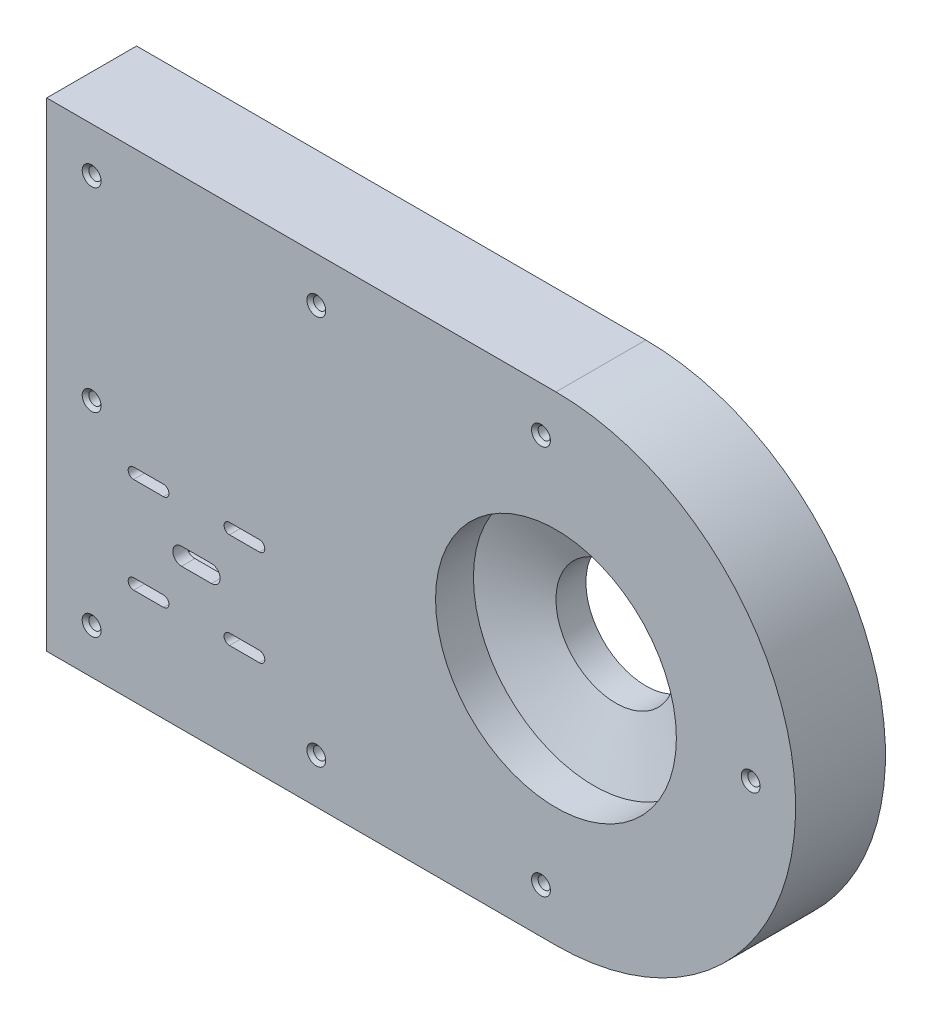
SolidWorks part; units mm, degrees
ref_plane "Front Plane" through (0, 0, 0) normal (0, 0, 1) x (1, 0, 0)
ref_plane "Top Plane" through (0, 0, 0) normal (0, 1, 0) x (1, 0, 0)
ref_plane "Right Plane" through (0, 0, 0) normal (1, 0, 0) x (0, 0, -1)
sketch "Sketch1" plane through (0, 0, 0) normal (0, 0, 1) x (1, 0, 0)
  line L0 (0, 80) -> (-170, 80)
  line L1 (-170, 80) -> (-170, -80)
  line L2 (-170, -80) -> (0, -80)
  arc A0 (0, -80) -> (0, 80) centre (0, 0) ccw
  circle A1 centre (-155, 65) radius 2.05
  circle A2 centre (-80, 65) radius 2.05
  circle A3 centre (-5, 65) radius 2.05
  circle A4 centre (-155, -65) radius 2.05
  circle A5 centre (-80, -65) radius 2.05
  circle A6 centre (-5, -65) radius 2.05
  circle A7 centre (-155, 0) radius 2.05
  circle A8 centre (65, 0) radius 2.05
  point P1 (80, 0)
  dimension "D1" = 250
  dimension "D2" = 80
  dimension "D6" = 65
  dimension "D7" = 220
  dimension "D10" = 4.1
  dimension "D3" = 75
  dimension "D4" = 75
  dimension "D5" = 65
  dimension "D8" = 15
  dimension "D9" = 15
extrude "Boss-Extrude1" add sketch "Sketch1" along normal mid plane 30
hole_wizard "CSK for M3 Flat Head Machine Screw1" positions "Sketch3" profile "Sketch4" countersink size "M3" standard "ANSI Metric" end condition through all
sketch "Sketch3" plane through (0, 0, 15) normal (0, 0, 1) x (1, 0, 0)
  point P0 (-5, -65)
  point P2 (-80, -65)
  point P4 (-155, -65)
  point P6 (-155, 0)
  point P8 (-155, 65)
  point P10 (-80, 65)
  point P12 (-5, 65)
  point P14 (65, 0)
sketch "Sketch4" plane through (-5, -65, 15) normal (1, 0, 0) x (0, -1, 0)
  line L0 (0, 0) -> (0, 30)
  line L1 (0, 30) -> (1.8, 30)
  line L2 (1.8, 30) -> (1.8, 1.35)
  line L3 (1.8, 1.35) -> (3.15, 0)
  line L5 (3.15, 0) -> (0, 0)
  line L6 (-1.8, 1.35) -> (-3.15, 0) construction
  line L11 (0, -6.35) -> (0, 107.95) construction
  dimension "Thru Hole Dia." = 3.6
  dimension "Thru Hole Depth" = 30
  dimension "Near C'Sink Dia." = 6.3
  dimension "Near C'Sink Angle" = 90
sketch "Sketch5" plane through (0, 0, -15) normal (0, 0, -1) x (-1, 0, 0)
  circle A0 centre (0, 0) radius 40.2
  arc A2 (0, 80) -> (0, -80) centre (0, 0) ccw construction
  point P9 (-80, 0)
  dimension "D1" = 80.4
extrude "Cut-Extrude1" cut sketch "Sketch5" against normal blind 20 from offset 10 offset against normal yes
sketch "Sketch6" plane through (0, 0, -15) normal (0, 0, -1) x (-1, 0, 0)
  circle A0 centre (0, 0) radius 20
  dimension "D1" = 40
extrude "Cut-Extrude2" cut sketch "Sketch6" against normal through all
sketch "Sketch7" plane through (0, 0, -15) normal (0, 0, -1) x (-1, 0, 0)
  line L1 (103.85, -51.15) -> (146.15, -51.15)
  line L2 (103.85, -51.15) -> (103.85, -8.85) construction
  line L3 (103.85, -8.85) -> (146.15, -8.85)
  line L4 (146.15, -51.15) -> (146.15, -8.85)
  line L5 (103.85, -51.15) -> (146.15, -8.85) construction
  line L6 (103.85, -8.85) -> (146.15, -51.15) construction
  line L7 (170, 80) -> (170, -80) construction
  line L8 (170, -80) -> (0, -80) construction
  line L9 (103.85, -8.85) -> (93.85, -8.85)
  line L10 (103.85, -8.85) -> (103.85, -51.15) construction
  line L11 (103.85, -51.15) -> (93.85, -51.15)
  line L12 (93.85, -8.85) -> (93.85, -51.15)
  line L13 (103.85, -8.85) -> (93.85, -51.15) construction
  line L14 (103.85, -51.15) -> (93.85, -8.85) construction
  point P4 (125, -30)
  point P10 (98.85, -30)
  dimension "D1" = 42.3
  dimension "D2" = 42.3
  dimension "D3" = 45
  dimension "D4" = 50
  dimension "D5" = 10
extrude "Cut-Extrude3" cut sketch "Sketch7" against normal offset from surface (22.27 mm away) 7.73 up to face at (-40.2, 0, 15)
hole_wizard "M3 Clearance Hole1" positions "Sketch9" profile "Sketch10" hole size "M3" standard "ANSI Metric" end condition through all
sketch "Sketch9" plane through (0, 0, 7.27) normal (0, 0, -1) x (-1, 0, 0)
  line L1 (141, -46) -> (109, -46)
  line L2 (141, -46) -> (141, -14)
  line L3 (141, -14) -> (109, -14)
  line L4 (109, -46) -> (109, -14)
  line L5 (141, -46) -> (109, -14) construction
  line L6 (141, -14) -> (109, -46) construction
  line L7 (146.15, -51.15) -> (146.15, -8.85) construction
  line L9 (146.15, -51.15) -> (146.15, -8.85) construction
  point P0 (109, -14)
  point P2 (141, -14)
  point P4 (141, -46)
  point P6 (109, -46)
  point P32 (125, -30)
  point P35 (146.15, -30)
  point P41 (99, -14)
  point P43 (99, -46)
  point P45 (131, -46)
  point P47 (131, -14)
  dimension "D1" = 32
  dimension "D2" = 32
  dimension "D3" = 21.15
  dimension "D4" = 10
  dimension "D5" = 10
sketch "Sketch10" plane through (-109, -14, 7.27) normal (1, 0, 0) x (0, 1, 0)
  line L0 (0, 0) -> (0, 7.73)
  line L1 (0, 7.73) -> (1.8, 7.73)
  line L2 (1.8, 7.73) -> (1.8, 0)
  line L5 (1.8, 0) -> (0, 0)
  line L11 (0, -6.35) -> (0, 107.95) construction
  dimension "Thru Hole Dia." = 3.6
  dimension "Thru Hole Depth" = 7.73
hole_wizard "M5 Clearance Hole1" positions "Sketch11" profile "Sketch12" hole size "M5" standard "ANSI Metric" end condition through all
sketch "Sketch11" plane through (0, 0, 7.27) normal (0, 0, -1) x (-1, 0, 0)
  line L2 (93.85, -8.85) -> (93.85, -51.15) construction
  line L3 (146.15, -51.15) -> (146.15, -8.85) construction
  point P0 (125, -30)
  point P14 (93.85, -30)
  point P17 (115, -30)
  dimension "D1" = 21.15
  dimension "D2" = 10
sketch "Sketch12" plane through (-125, -30, 7.27) normal (1, 0, 0) x (0, 1, 0)
  line L0 (0, 0) -> (0, 7.73)
  line L1 (0, 7.73) -> (2.9, 7.73)
  line L2 (2.9, 7.73) -> (2.9, 0)
  line L5 (2.9, 0) -> (0, 0)
  line L11 (0, -6.35) -> (0, 107.95) construction
  dimension "Thru Hole Dia." = 5.8
  dimension "Thru Hole Depth" = 7.73
sketch "Sketch13" plane through (0, 0, 7.27) normal (0, 0, -1) x (-1, 0, 0)
  line L0 (115, -18.85) -> (125, -18.85)
  line L1 (125, -41.15) -> (115, -41.15)
  arc A0 (125, -41.15) -> (125, -18.85) centre (125, -30) ccw
  arc A1 (115, -18.85) -> (115, -41.15) centre (115, -30) ccw
  circle A2 centre (115, -30) radius 2.9 construction
  arc A3 (120, -20.0339) -> (120, -39.9661) centre (125, -30) ccw construction
  arc A4 (120, -39.9661) -> (120, -20.0339) centre (115, -30) ccw construction
  arc A5 (120, -39.9661) -> (125, -41.15) centre (125, -30) ccw construction
  arc A6 (115, -41.15) -> (120, -39.9661) centre (115, -30) ccw construction
  arc A7 (120, -20.0339) -> (115, -18.85) centre (115, -30) ccw construction
  arc A8 (125, -18.85) -> (120, -20.0339) centre (125, -30) ccw construction
  dimension "D1" = 22.3
extrude "Cut-Extrude4" cut sketch "Sketch13" against normal blind 3.27
sketch "Sketch14" plane through (0, 0, 7.27) normal (0, 0, -1) x (-1, 0, 0)
  line L0 (115, -30) -> (125, -30) construction
  line L1 (115, -27.1) -> (125, -27.1)
  line L2 (115, -32.9) -> (125, -32.9)
  line L3 (99, -14) -> (109, -14) construction
  line L4 (99, -12.2) -> (109, -12.2)
  line L5 (99, -15.8) -> (109, -15.8)
  line L6 (131, -14) -> (141, -14) construction
  line L7 (131, -12.2) -> (141, -12.2)
  line L8 (131, -15.8) -> (141, -15.8)
  line L9 (141, -46) -> (131, -46) construction
  line L10 (141, -47.8) -> (131, -47.8)
  line L11 (141, -44.2) -> (131, -44.2)
  line L12 (109, -46) -> (99, -46) construction
  line L13 (109, -47.8) -> (99, -47.8)
  line L14 (109, -44.2) -> (99, -44.2)
  arc A0 (115, -27.1) -> (115, -32.9) centre (115, -30) ccw
  arc A1 (125, -32.9) -> (125, -27.1) centre (125, -30) ccw
  circle A2 centre (125, -30) radius 2.9 construction
  arc A3 (99, -12.2) -> (99, -15.8) centre (99, -14) ccw
  arc A4 (109, -15.8) -> (109, -12.2) centre (109, -14) ccw
  arc A5 (131, -12.2) -> (131, -15.8) centre (131, -14) ccw
  arc A6 (141, -15.8) -> (141, -12.2) centre (141, -14) ccw
  arc A7 (141, -47.8) -> (141, -44.2) centre (141, -46) ccw
  arc A8 (131, -44.2) -> (131, -47.8) centre (131, -46) ccw
  arc A9 (109, -47.8) -> (109, -44.2) centre (109, -46) ccw
  arc A10 (99, -44.2) -> (99, -47.8) centre (99, -46) ccw
  circle A11 centre (99, -46) radius 1.8 construction
  point P2 (120, -30)
  point P8 (104, -14)
  point P20 (136, -14)
  point P29 (136, -46)
  point P38 (104, -46)
extrude "Cut-Extrude5" cut sketch "Sketch14" against normal through all
sketch "Sketch15" plane through (0, 0, -15) normal (0, 0, -1) x (-1, 0, 0)
  circle A0 centre (0, 0) radius 45.15
  circle A1 centre (0, 0) radius 32.35
  dimension "D1" = 90.3
  dimension "D2" = 64.7
extrude "Cut-Extrude6" cut sketch "Sketch15" against normal blind 2
sketch "Sketch16" plane through (0, 0, 0) normal (0, 1, 0) x (1, 0, 0)
  line L0 (20, 5) -> (40.2, 5)
  line L1 (40.2, 5) -> (40.2, -2.3522)
  line L2 (40.2, -2.3522) -> (20, 5)
  line L3 (-20, 5) -> (20, 5) construction
  line L4 (-20, 5) -> (20, 5) construction
  line L5 (0, 9.0692) -> (0, 0) construction
  point P2 (0, 0)
  point P3 (0, 6.4452)
  point P5 (12.532, 5)
  point P7 (0, 1.0948)
  point P10 (0, 0)
  point P12 (0, 0)
  point P13 (0, 0)
  dimension "D1" = 70
revolve "Revolve3" add sketch "Sketch16" angle 360 about L5
